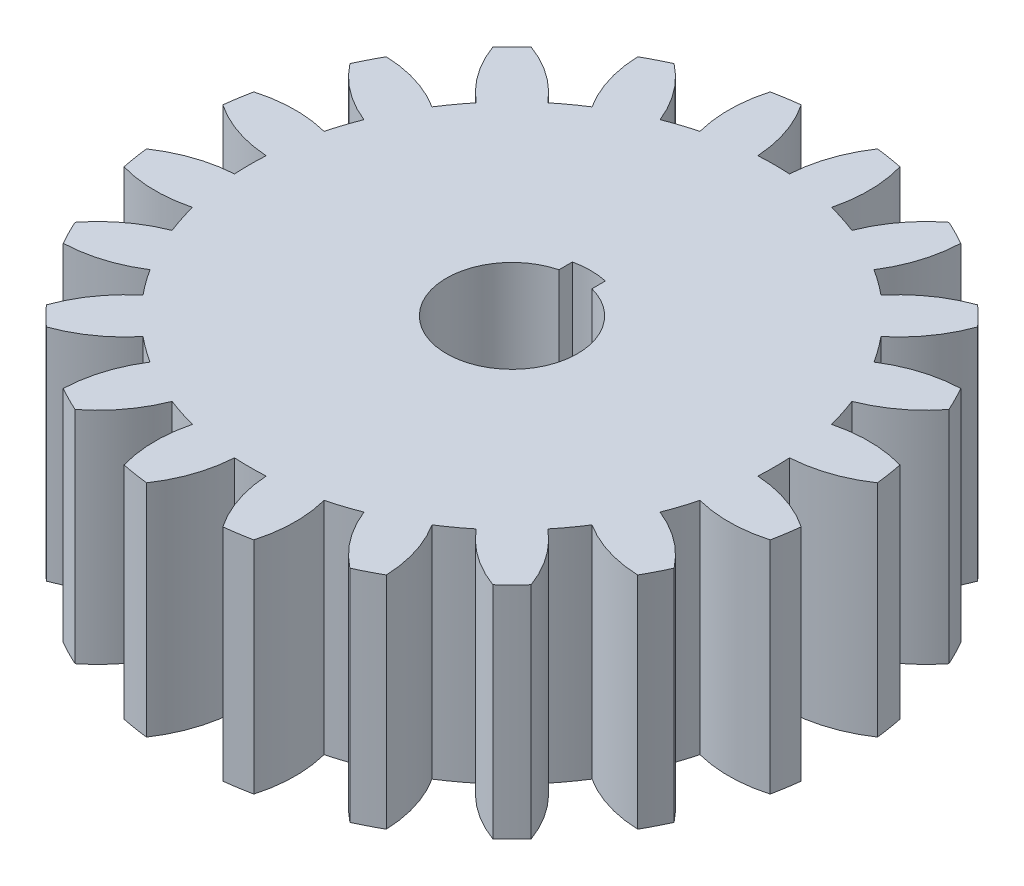
SolidWorks part; units mm, degrees
ref_plane "Ön Düzlem" through (0, 0, 0) normal (0, 0, 1) x (1, 0, 0)
ref_plane "Üst Düzlem" through (0, 0, 0) normal (0, 1, 0) x (1, 0, 0)
ref_plane "Sağ Düzlem" through (0, 0, 0) normal (1, 0, 0) x (0, 0, -1)
sketch "Çizim2" plane through (0, 0, 0) normal (0, 1, 0) x (1, 0, 0)
  line L0 (0, 0) -> (0, 55) construction
  line L1 (-3.923, 49.8459) -> (3.923, 49.8459) construction
  line L2 (0, 0) -> (17.2208, 41.5746) construction
  line L3 (-2.6407, 43.6702) -> (0, 0) construction
  line L4 (3.923, 49.8459) -> (11.6723, 48.6185) construction
  line L5 (0, 0) -> (7.0396, 44.446) construction
  line L6 (-5.6914, 54.7047) -> (0, 39.0676) construction
  circle A0 centre (0, 0) radius 50 construction
  arc A1 (16.7424, 40.4197) -> (6.844, 43.2114) centre (0, 0) ccw
  arc A2 (6.3647, 54.6305) -> (-6.3647, 54.6305) centre (0, 0) ccw
  arc A6 (-6.3647, 54.6305) -> (-2.6407, 43.6702) centre (-24.5263, 42.3469) cw
  arc A7 (6.3647, 54.6305) -> (2.6407, 43.6702) centre (24.5263, 42.3469) ccw
  arc A8 (3.0752, 46.8839) -> (-3.0752, 46.8839) centre (0, 0) ccw
  arc A9 (2.6407, 43.6702) -> (-2.6407, 43.6702) centre (0, 0) ccw
  dimension "D1" = 100
  dimension "D2" = 87.5
  dimension "D3" = 110
  dimension "D5" = 46.9846
  dimension "D4" = 22.5
  dimension "D6" = 9
  dimension "D7" = 20
sketch "Çizim4" plane through (0, 0, 0) normal (0, 1, 0) x (1, 0, 0)
  circle A0 centre (0, 0) radius 55
  dimension "D1" = 110
extrude "Yükseklik-Ekstrüzyon1" add sketch "Çizim4" along normal mid plane 36.75
extrude "Kes-Ekstrüzyon2" cut sketch "Çizim2" against normal mid plane 50 contours A7 A9 A6 A2
pattern_circular "Dairesel Kaplama2" count 20 over 360 about axis through (0, 0, 0) along (0, 1, 0) of "Kes-Ekstrüzyon2"
sketch "Çizim9" plane through (0, 18.375, 0) normal (0, 1, 0) x (1, 0, 0)
  line L0 (2.75, 10.5861) -> (2.75, 12.8337)
  line L1 (-2.75, 10.5861) -> (-2.75, 12.8337)
  line L2 (-2.75, 11.7099) -> (2.75, 11.7099) construction
  arc A0 (2.75, 12.8337) -> (-2.75, 12.8337) centre (0, 0) ccw
  arc A1 (-2.75, 10.5861) -> (2.75, 10.5861) centre (0, 0) ccw
  dimension "D1" = 26.25
  dimension "D2" = 21.875
  dimension "D3" = 5.5
extrude "Kes-Ekstrüzyon3" cut sketch "Çizim9" against normal up to surface (36.75 mm away) up to face at (0, -18.375, 0)
equation "\"m\" = 5"
equation "\"z\" = 20"
equation "\"n\"= 600"
equation "\"nv\"= 0.9"
equation "\"t\"= 15"
equation "\"Vg\"= 1.2"
equation "\"Vç\"= 4.5"
equation "\"D\"= 180"
equation "\"Ddd\"= 12"
equation "\"Ds\"= 4"
equation "\"Dd\"= 8"
equation "\"df\"= \"m\" * \"z\" - 2.5 * \"m\""
equation "\"b\"= 10 * \"m\""
equation "\"P\"= 3"
equation "\"ηr\"= 0.85"
equation "\"Vo\"= 3.1416 * \"df\" * \"m\" * \"b\" / ( \"z\" * 1000 )"
equation "\"V\"= 2 * \"z\" * \"Vo\""
equation "\"Qt\"= \"V\" * \"n\" / 1000"
equation "\"Qe\"= \"Qt\" * \"nv\""
equation "\"Δp\"= \"P\" * \"ηr\" * 600 / \"Qe\""
equation "\"D1@Çizim2\"= \"m\" * \"z\""
equation "\"dk\"= \"m\" * \"z\" + 2 * \"m\""
equation "\"D2@Çizim2\"=\"df\""
equation "\"D1@Yükseklik-Ekstrüzyon1\"= \"m\" * 14.7 / 2"
equation "\"D1@Çizim4\"= \"dk\""
equation "\"alfa\"= 20derece'basma açısı"
equation "\"rb\"= \"m\" * \"z\" * cos ( \"alfa\" ) / 2mm"
equation "\"D1@Kes-Ekstrüzyon2\"=\"m\"*10"
equation "\"D1@Çizim9\"=\"df\"*0.3"
equation "\"D2@Çizim9\"=\"df\"*0.25"
equation "\"D1@Dairesel Kaplama2\"=\"z\""
equation "\"D5@Çizim2\"=\"rb\""
equation "\"D3@Çizim2\"=\"dk\""
equation "\"D3@Çizim9\"=\"dk\"*0.05"
equation "\"D6@Çizim2\"=180/\"z\""
